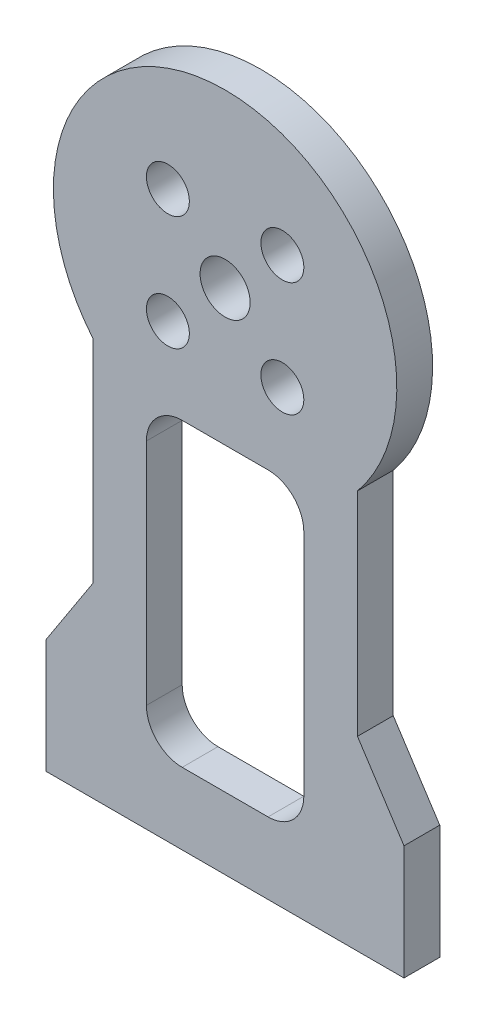
SolidWorks part; units mm, degrees
ref_plane "Płaszczyzna przednia" through (0, 0, 0) normal (0, 0, 1) x (1, 0, 0)
ref_plane "Płaszczyzna górna" through (0, 0, 0) normal (0, 1, 0) x (1, 0, 0)
ref_plane "Płaszczyzna prawa" through (0, 0, 0) normal (1, 0, 0) x (0, 0, -1)
sketch "Szkic1" plane through (0, 0, 0) normal (0, 0, 1) x (1, 0, 0)
  line L0 (0, 0) -> (0, 47.5) construction
  line L1 (12.5, 0) -> (-12.5, 0)
  line L2 (-12.5, 0) -> (-12.5, 8)
  line L3 (-12.5, 8) -> (-9.25, 13)
  line L4 (-9.25, 13) -> (-9.25, 27.8556)
  line L5 (3, 5) -> (-3, 5)
  line L6 (-5.5, 7.5) -> (-5.5, 23.5)
  line L7 (-3, 26) -> (3, 26)
  line L8 (-12, 35.5) -> (12, 35.5) construction
  line L9 (5.5, 7.5) -> (5.5, 23.5)
  line L10 (9.25, 13) -> (9.25, 27.8556)
  line L11 (12.5, 8) -> (9.25, 13)
  line L12 (12.5, 0) -> (12.5, 8)
  arc A0 (9.25, 27.8556) -> (-9.25, 27.8556) centre (0, 35.5) ccw
  circle A1 centre (0, 35.5) radius 1.75
  circle A2 centre (-4, 39.5) radius 1.5
  circle A3 centre (-4, 31.5) radius 1.5
  arc A4 (-5.5, 23.5) -> (-3, 26) centre (-3, 23.5) cw
  arc A5 (-3, 5) -> (-5.5, 7.5) centre (-3, 7.5) cw
  arc A6 (3, 5) -> (5.5, 7.5) centre (3, 7.5) ccw
  arc A7 (5.5, 23.5) -> (3, 26) centre (3, 23.5) ccw
  circle A8 centre (4, 31.5) radius 1.5
  circle A9 centre (4, 39.5) radius 1.5
  point P25 (0, 26)
  point P26 (0, 5)
  dimension "D2" = 24
  dimension "D10" = 3
  dimension "D11" = 3.5
  dimension "D12" = 4
  dimension "D13" = 4
  dimension "D14" = 2.5
  dimension "D3" = 8
  dimension "D4" = 5
  dimension "D5" = 12.5
  dimension "D6" = 9.25
  dimension "D7" = 5.5
  dimension "D8" = 5
  dimension "D9" = 21
  dimension "D15" = 47.5
extrude "Dodanie-wyciągnięcie1" add sketch "Szkic1" along normal blind 2.5
